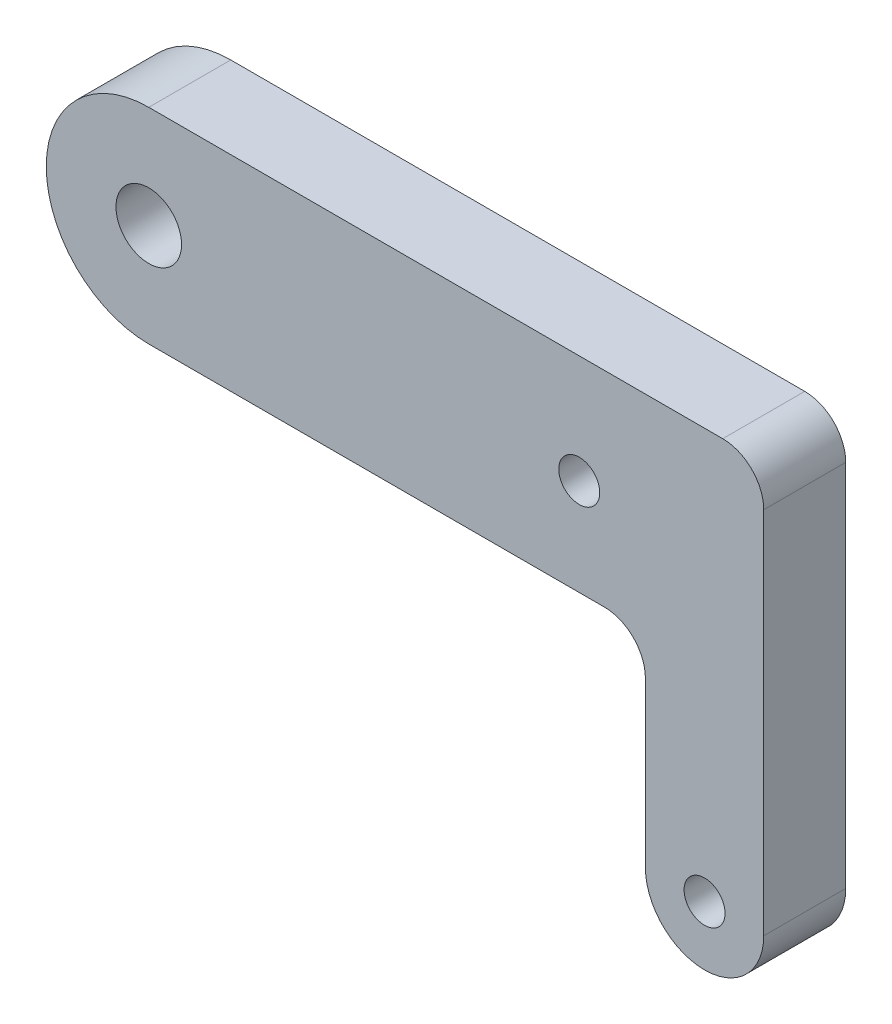
SolidWorks part; units mm, degrees
ref_plane "Front Plane" through (0, 0, 0) normal (0, 0, 1) x (1, 0, 0)
ref_plane "Top Plane" through (0, 0, 0) normal (0, 1, 0) x (1, 0, 0)
ref_plane "Right Plane" through (0, 0, 0) normal (1, 0, 0) x (0, 0, -1)
sketch "Sketch1" plane through (0, 0, 0) normal (0, 0, 1) x (1, 0, 0)
  line L0 (-10, 0) -> (-150, 0)
  line L1 (-38.8675, -50) -> (-150, -50)
  line L2 (-28.8675, -60) -> (-28.8675, -100)
  line L4 (0, -10) -> (0, -100)
  line L5 (46.1631, 11.8664) -> (41.0508, 11.8664) construction
  arc A0 (-150, 0) -> (-150, -50) centre (-150, -25) ccw
  circle A1 centre (-150, -25) radius 8
  arc A2 (-28.8675, -100) -> (0, -100) centre (-14.4338, -100) ccw
  circle A3 centre (-14.4338, -100) radius 5
  arc A4 (-38.8675, -50) -> (-28.8675, -60) centre (-38.8675, -60) cw
  arc A5 (-10, 0) -> (0, -10) centre (-10, -10) cw
  point P15 (-28.8675, -50)
  point P18 (0, 0)
  dimension "D1" = 50
  dimension "D2" = 16
  dimension "D3" = 150
  dimension "D6" = 10
  dimension "D4" = 10
  dimension "D5" = 90
  dimension "D7" = 50
extrude "Boss-Extrude1" add sketch "Sketch1" along normal blind 20
sketch "Sketch2" plane through (0, 0, 20) normal (0, 0, 1) x (1, 0, 0)
  line L0 (0, -100) -> (0, -10) construction
  circle A0 centre (-45, -26.4068) radius 5
  dimension "D1" = 10
  dimension "D2" = 45
extrude "Cut-Extrude1" cut sketch "Sketch2" against normal blind 35
